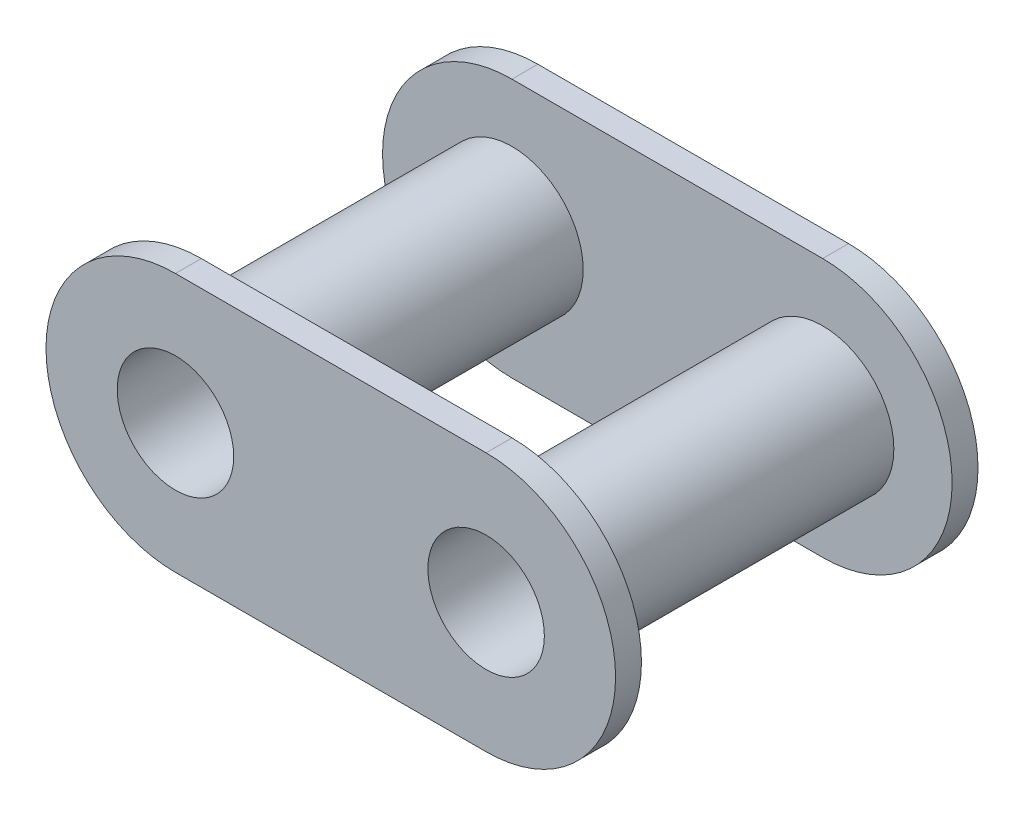
SolidWorks part; units mm, degrees
ref_plane "Front Plane" through (0, 0, 0) normal (0, 0, 1) x (1, 0, 0)
ref_plane "Top Plane" through (0, 0, 0) normal (0, 1, 0) x (1, 0, 0)
ref_plane "Right Plane" through (0, 0, 0) normal (1, 0, 0) x (0, 0, -1)
sketch "Sketch1" plane through (0, 0, 0) normal (0, 0, 1) x (1, 0, 0)
  line L0 (-3, 0) -> (3, 0) construction
  line L1 (-3, 2.5) -> (3, 2.5)
  line L2 (-3, -2.5) -> (3, -2.5)
  arc A0 (-3, 2.5) -> (-3, -2.5) centre (-3, 0) ccw
  arc A1 (3, -2.5) -> (3, 2.5) centre (3, 0) ccw
  circle A2 centre (-3, 0) radius 1.125
  circle A3 centre (3, 0) radius 1.125
  point P3 (0, 0)
  dimension "D2" = 2.5
  dimension "D3" = 2.25
  dimension "D1" = 6
extrude "Boss-Extrude1" add sketch "Sketch1" along normal blind 0.5
sketch "Sketch2" plane through (0, 0, 0.5) normal (0, 0, 1) x (1, 0, 0)
  circle A0 centre (-3, 0) radius 1.125 construction
  circle A1 centre (-3, 0) radius 1.125
  circle A2 centre (3, 0) radius 1.125 construction
  circle A3 centre (3, 0) radius 1.125
extrude "Extrude-Thin1" add sketch "Sketch2" along normal blind 3 thin
ref_plane "Plane1" through (0, 0, 3.5) normal (0, 0, 1) x (1, 0, 0)
mirror "Mirror1" about plane through (0, 0, 3.5) normal (0, 0, 1) of "Boss-Extrude1", "Extrude-Thin1"
